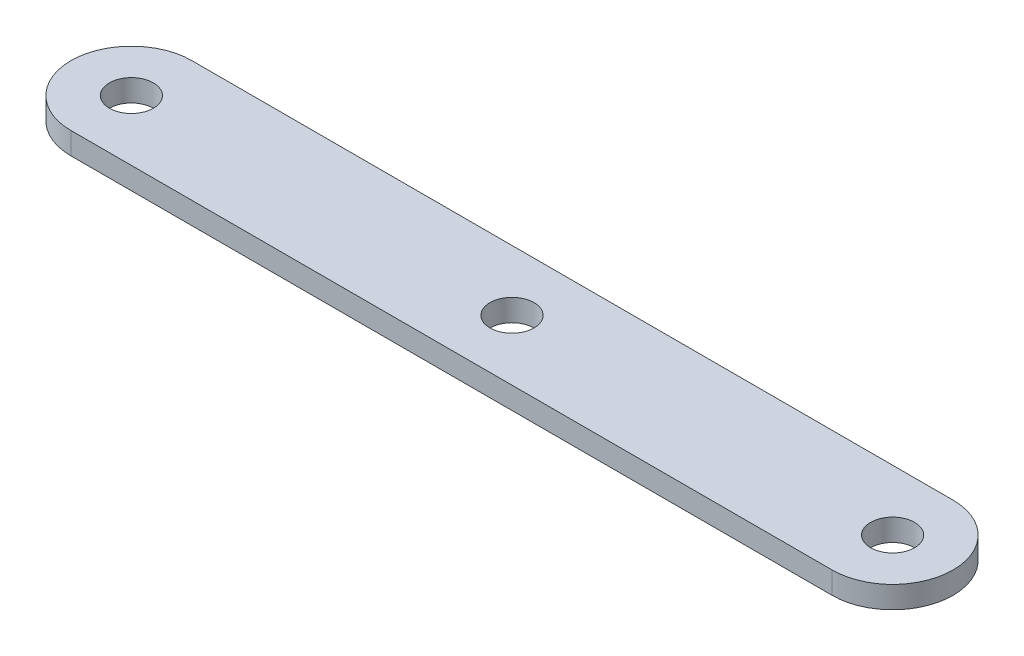
SolidWorks part; units mm, degrees
ref_plane "Front Plane" through (0, 0, 0) normal (0, 0, 1) x (1, 0, 0)
ref_plane "Top Plane" through (0, 0, 0) normal (0, 1, 0) x (1, 0, 0)
ref_plane "Right Plane" through (0, 0, 0) normal (1, 0, 0) x (0, 0, -1)
sketch "Sketch2" plane through (0, 0, 0) normal (0, 1, 0) x (1, 0, 0)
  line L0 (-34.61, 0) -> (34.61, 0) construction
  line L1 (-34.61, 5.5) -> (34.61, 5.5)
  line L2 (-34.61, -5.5) -> (34.61, -5.5)
  arc A0 (-34.61, 5.5) -> (-34.61, -5.5) centre (-34.61, 0) ccw
  arc A1 (34.61, -5.5) -> (34.61, 5.5) centre (34.61, 0) ccw
  circle A2 centre (-34.61, 0) radius 2
  circle A3 centre (34.61, 0) radius 2
  circle A4 centre (0, 0) radius 2
  point P2 (0, 0)
  dimension "D2" = 4
  dimension "D3" = 4
  dimension "D4" = 5.5
  dimension "D5" = 4
  dimension "D1" = 69.22
extrude "Boss-Extrude1" add sketch "Sketch2" along normal blind 2
